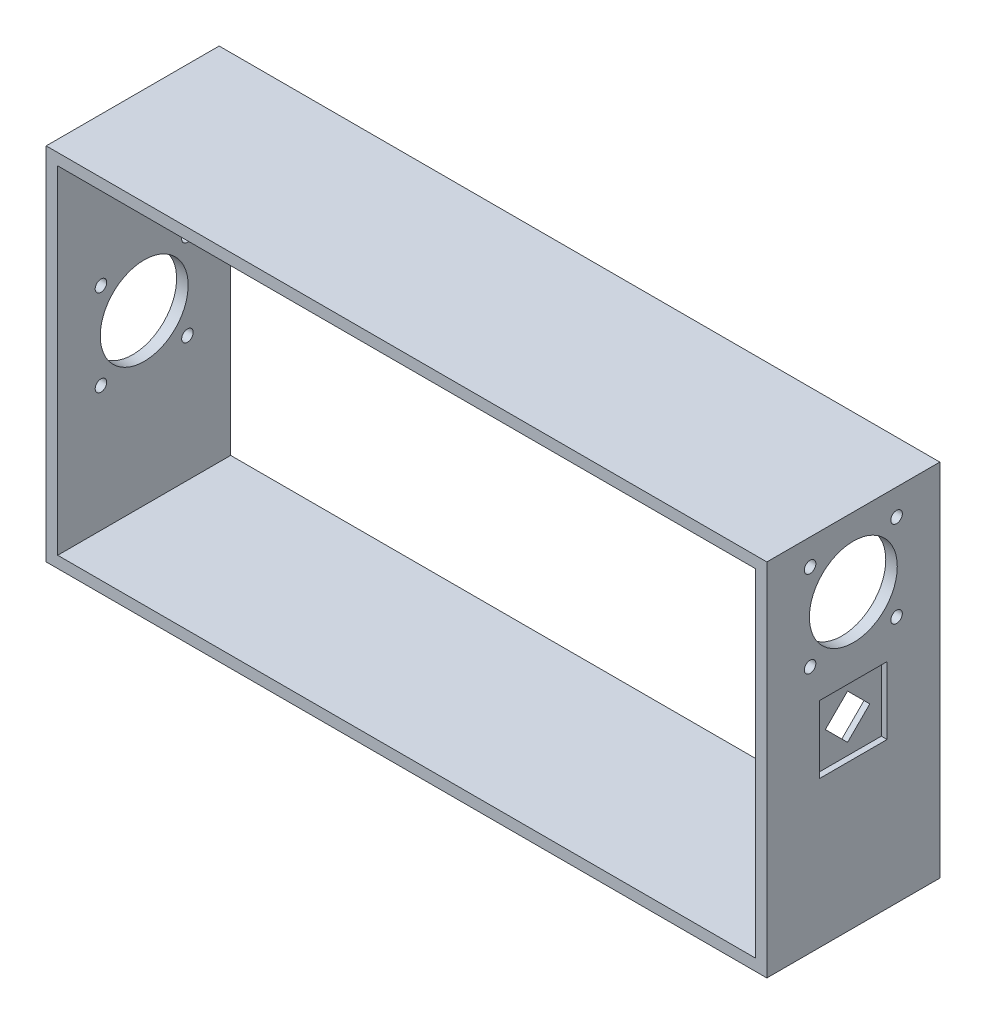
SolidWorks part; units mm, degrees
ref_plane "Ebene vorne" through (0, 0, 0) normal (0, 0, 1) x (1, 0, 0)
ref_plane "Ebene oben" through (0, 0, 0) normal (0, 1, 0) x (1, 0, 0)
ref_plane "Ebene rechts" through (0, 0, 0) normal (1, 0, 0) x (0, 0, -1)
sketch "Skizze1" plane through (0, 0, 0) normal (0, 0, 1) x (1, 0, 0)
  line L1 (0, 125) -> (250, 125)
  line L2 (0, 125) -> (0, 0)
  line L3 (0, 0) -> (250, 0)
  line L4 (250, 125) -> (250, 0)
  line L5 (246, 121) -> (4, 121)
  line L6 (246, 121) -> (246, 4)
  line L7 (246, 4) -> (4, 4)
  line L8 (4, 121) -> (4, 4)
  dimension "D1" = 250
  dimension "D2" = 125
  dimension "D3" = 4
  dimension "D4" = 4
  dimension "D5" = 4
  dimension "D6" = 4
extrude "Aufsatz-Linear austragen1" add sketch "Skizze1" along normal blind 60
sketch "Skizze2" plane through (0, 0, 0) normal (-1, 0, 0) x (0, 0, 1)
  line L0 (0, 62.5) -> (60, 62.5) construction
  line L1 (30, 125) -> (30, 0) construction
  line L2 (60, 125) -> (0, 125) construction
  line L3 (60, 0) -> (0, 0) construction
  line L4 (0, 125) -> (0, 0) construction
  line L5 (60, 125) -> (60, 0) construction
  line L6 (15, 77.5) -> (45, 77.5) construction
  line L7 (45, 77.5) -> (45, 47.5) construction
  line L8 (45, 47.5) -> (15, 47.5) construction
  line L9 (15, 47.5) -> (15, 77.5) construction
  circle A0 centre (30, 62.5) radius 15.25
  circle A1 centre (15, 77.5) radius 2
  circle A2 centre (45, 77.5) radius 2
  circle A3 centre (45, 47.5) radius 2
  circle A4 centre (15, 47.5) radius 2
  point P17 (30, 62.5)
  point P21 (30, 77.5)
  point P22 (53.5816, 62.5)
  point P24 (15, 62.5)
  dimension "D1" = 30
  dimension "D2" = 30
extrude "Schnitt-Linear austragen1" cut sketch "Skizze2" against normal blind 10
sketch "Skizze8" plane through (250, 0, 0) normal (1, 0, 0) x (0, 0, -1)
  line L0 (-60, 62.5) -> (0, 62.5) construction
  line L1 (-60, 0) -> (-60, 125) construction
  line L2 (0, 0) -> (0, 125) construction
  line L3 (-30, 125) -> (-30, 0) construction
  line L4 (-60, 125) -> (0, 125) construction
  line L5 (-60, 0) -> (0, 0) construction
  line L6 (-30, 70.2075) -> (-37.7075, 62.5)
  line L11 (-30, 70.2075) -> (-22.2925, 62.5)
  line L12 (-37.7075, 62.5) -> (-30, 54.7925)
  line L13 (-22.2925, 62.5) -> (-30, 54.7925)
  line L14 (-30, 70.2075) -> (-30, 54.7925) construction
  line L15 (-37.7075, 62.5) -> (-22.2925, 62.5) construction
  line L16 (-45, 116) -> (-15, 116) construction
  line L25 (-45, 116) -> (-15, 86) construction
  line L26 (-45, 86) -> (-15, 116) construction
  line L27 (-15, 116) -> (-15, 86) construction
  line L28 (-15, 86) -> (-45, 86) construction
  line L29 (-45, 86) -> (-45, 116) construction
  circle A0 centre (-30, 101) radius 15.25
  circle A1 centre (-45, 116) radius 2
  circle A2 centre (-15, 86) radius 2
  circle A3 centre (-45, 86) radius 2
  circle A4 centre (-15, 116) radius 2
  point P12 (-30, 101)
  point P13 (-30, 62.5)
  point P24 (0, 0)
  point P26 (0, 0)
  point P27 (0, 0)
  point P31 (0, 0)
  point P33 (0, 0)
  dimension "D3" = 30
  dimension "D4" = 30
  dimension "D1" = 10.9
  dimension "D2" = 10.9
  dimension "D5" = 24
extrude "Schnitt-Linear austragen6" cut sketch "Skizze8" against normal blind 22
sketch "Skizze9" plane through (250, 0, 0) normal (1, 0, 0) x (0, 0, -1)
sketch "Skizze10" plane through (250, 0, 0) normal (1, 0, 0) x (0, 0, -1)
  line L1 (-41.7075, 74.2075) -> (-18.2925, 74.2075)
  line L2 (-41.7075, 74.2075) -> (-41.7075, 50.7925)
  line L3 (-41.7075, 50.7925) -> (-18.2925, 50.7925)
  line L4 (-18.2925, 74.2075) -> (-18.2925, 50.7925)
  dimension "D1" = 4
  dimension "D2" = 4
  dimension "D3" = 4
  dimension "D4" = 4
extrude "Schnitt-Linear austragen7" cut sketch "Skizze10" against normal blind 2
